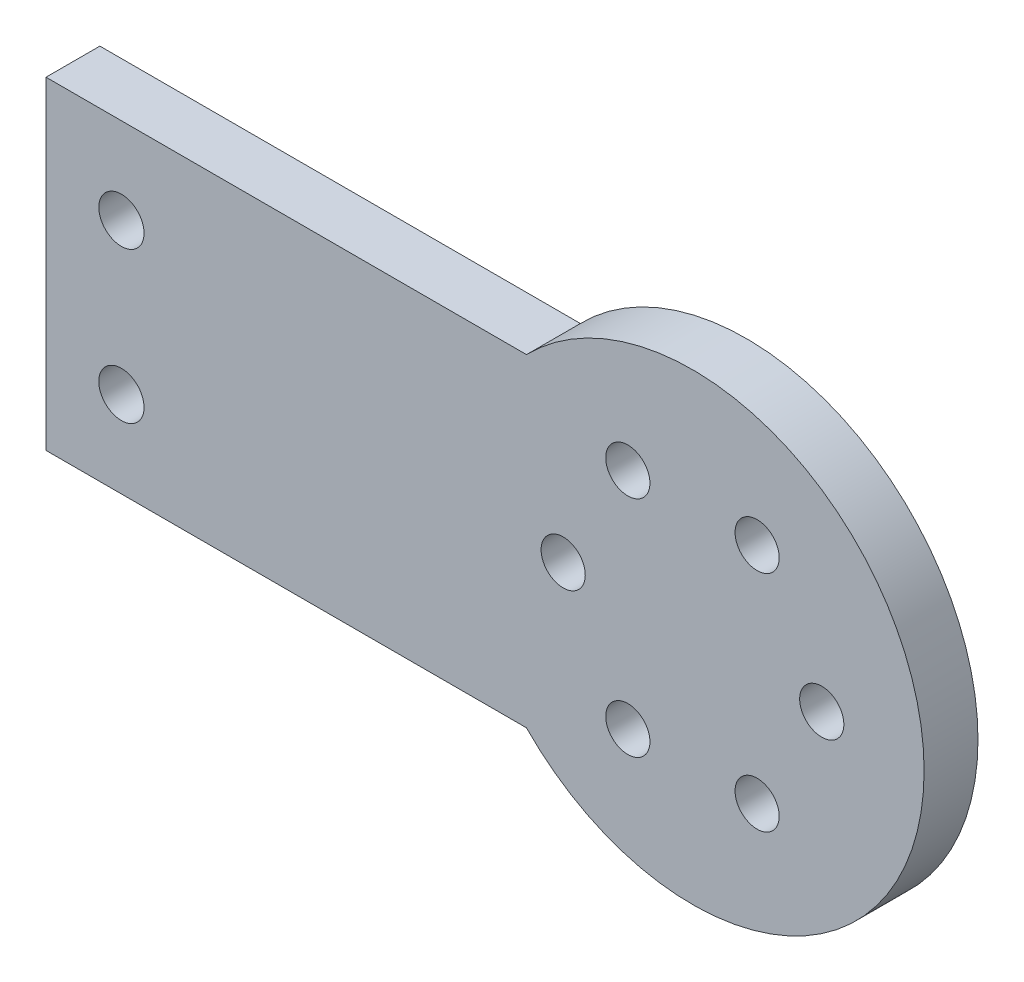
SolidWorks part; units mm, degrees
material "Thornel Mat VMA"
ref_plane "前视基准面" through (0, 0, 0) normal (0, 0, 1) x (1, 0, 0)
ref_plane "上视基准面" through (0, 0, 0) normal (0, 1, 0) x (1, 0, 0)
ref_plane "右视基准面" through (0, 0, 0) normal (1, 0, 0) x (0, 0, -1)
other "Configuration Table"
sketch "草图1" plane through (0, 0, 0) normal (0, 0, 1) x (1, 0, 0)
  line L0 (0, 0) -> (21.5, 0) construction
  line L1 (0, 0) -> (12, 0) construction
  line L2 (0, 0) -> (-60, 0) construction
  line L3 (-60, 0) -> (-60, 15)
  line L4 (-60, 15) -> (-15.4029, 15)
  line L5 (-60, 0) -> (-60, -15)
  line L6 (-60, -15) -> (-15.4029, -15)
  circle A0 centre (0, 0) radius 21.5 construction
  circle A1 centre (12, 0) radius 2.05
  circle A2 centre (6, -10.3923) radius 2.05
  circle A3 centre (-6, -10.3923) radius 2.05
  circle A4 centre (-12, 0) radius 2.05
  circle A5 centre (-6, 10.3923) radius 2.05
  circle A6 centre (6, 10.3923) radius 2.05
  arc A7 (-15.4029, 15) -> (-15.4029, -15) centre (0, 0) cw
  dimension "D1" = 43
  dimension "D2" = 4.1
  dimension "D5" = 60
  dimension "D3" = 12
  dimension "D6" = 15
  dimension "D7" = 15
  dimension "D4" = 6
extrude "凸台-拉伸1" add sketch "草图1" along normal blind 5
sketch "草图2" plane through (0, 0, 5) normal (0, 0, 1) x (1, 0, 0)
  line L0 (-60, 15) -> (-60, -15) construction
  circle A0 centre (-53, 7) radius 2.1
  circle A1 centre (-53, -7) radius 2.1
  point P6 (-60, 0)
  dimension "D1" = 4.2
  dimension "D2" = 4.2
  dimension "D3" = 7
  dimension "D4" = 7
  dimension "D5" = 7
  dimension "D6" = 7
extrude "切除-拉伸1" cut sketch "草图2" against normal through all
